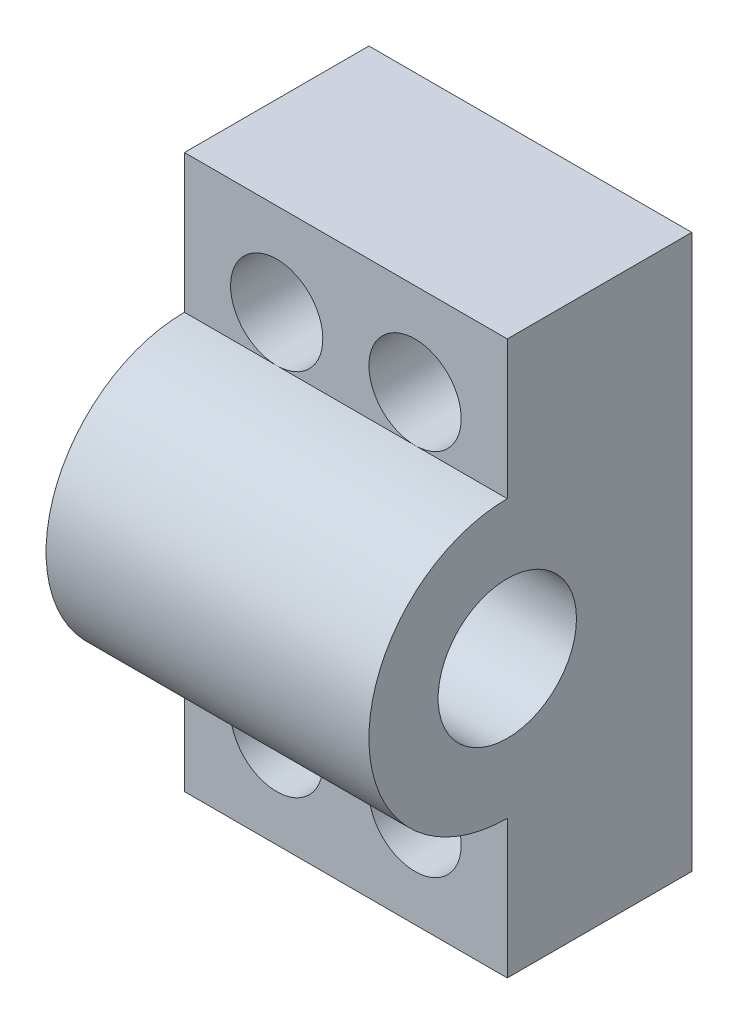
SolidWorks part; units mm, degrees
ref_plane "Front Plane" through (0, 0, 0) normal (0, 0, 1) x (1, 0, 0)
ref_plane "Top Plane" through (0, 0, 0) normal (0, 1, 0) x (1, 0, 0)
ref_plane "Right Plane" through (0, 0, 0) normal (1, 0, 0) x (0, 0, -1)
sketch "Sketch1" plane through (0, 0, 0) normal (1, 0, 0) x (0, 0, -1)
  line L0 (0, -30) -> (0, 30)
  line L1 (0, 30) -> (-20, 30)
  line L2 (-20, 30) -> (-20, 15)
  line L3 (-20, -15) -> (-20, -30)
  line L4 (-20, -30) -> (0, -30)
  line L5 (0, 0) -> (-35, 0) construction
  arc A0 (-20, 15) -> (-20, -15) centre (-20, 0) ccw
  point P0 (0, 0)
  dimension "D1" = 15
  dimension "D2" = 20
  dimension "D3" = 60
extrude "body" add sketch "Sketch1" along normal blind 35
sketch "Sketch2" plane through (0, 0, 0) normal (0, 0, 1) x (1, 0, 0)
  line L0 (0, 0) -> (35, 0) construction
  line L1 (0, 15) -> (0, -15) construction
  line L2 (35, -15) -> (35, 15) construction
  line L3 (17.5, -30) -> (17.5, 30) construction
  line L4 (35, -30) -> (0, -30) construction
  line L5 (35, 30) -> (0, 30) construction
  circle A0 centre (10, 20) radius 5
  circle A1 centre (25, 20) radius 5
  circle A2 centre (10, -20) radius 5
  circle A3 centre (25, -20) radius 5
  dimension "D1" = 10
  dimension "D3" = 15
  dimension "D2" = 20
extrude "fixing holes" cut sketch "Sketch2" along normal through all
sketch "Sketch3" plane through (35, 0, 0) normal (1, 0, 0) x (0, 0, -1)
  circle A0 centre (-20, 0) radius 7.5
  arc A2 (-20, 15) -> (-20, -15) centre (-20, 0) ccw construction
  point P2 (0, 0)
  point P3 (-13.0583, 0)
  point P4 (-12.5, 0)
  point P6 (-10, 0)
  dimension "D1" = 15
extrude "shaft hole" cut sketch "Sketch3" against normal blind 40
